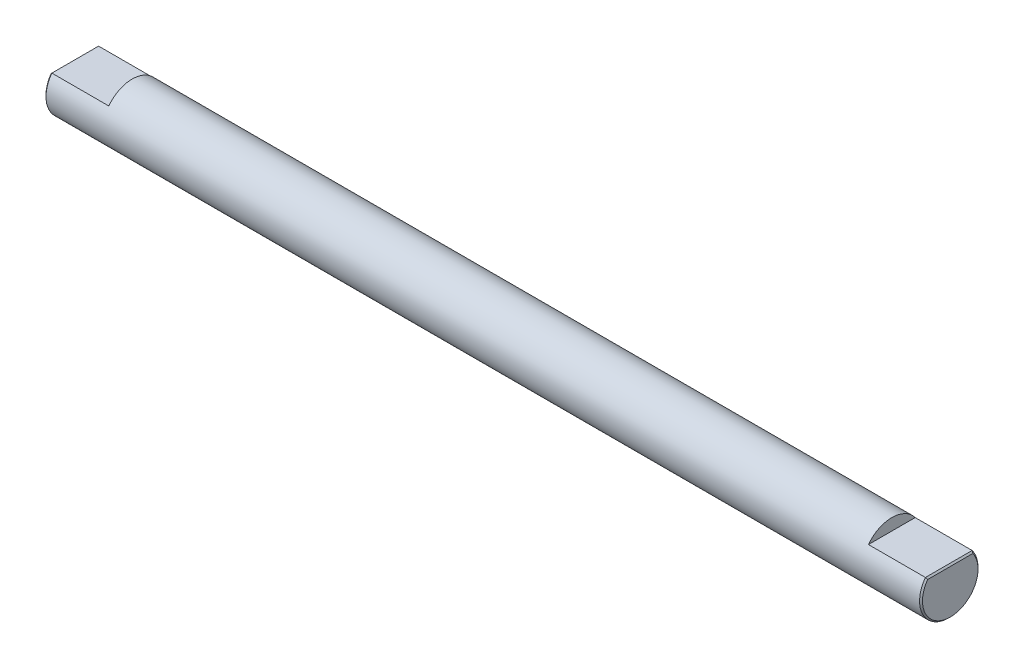
SolidWorks part; units mm, degrees
ref_plane "Front Plane" through (0, 0, 0) normal (0, 0, 1) x (1, 0, 0)
ref_plane "Top Plane" through (0, 0, 0) normal (0, 1, 0) x (1, 0, 0)
ref_plane "Right Plane" through (0, 0, 0) normal (1, 0, 0) x (0, 0, -1)
sketch "Sketch1" plane through (0, 0, 0) normal (0, 0, 1) x (1, 0, 0)
  line L0 (0, 0) -> (300, 0) construction
  line L2 (0, 0) -> (300, 0)
  line L3 (0, 0) -> (0, 10)
  line L4 (0, 10) -> (300, 10)
  line L5 (300, 0) -> (300, 10)
  dimension "D" = 20
  dimension "L" = 300
revolve "Revolve1" add sketch "Sketch1" angle 360 about L0
sketch "Sketch2" plane through (0, 0, 0) normal (0, 0, 1) x (1, 0, 0)
  line L0 (0, 10) -> (300, 10) construction
  line L1 (0, 10) -> (20, 10)
  line L2 (0, 10) -> (0, 6)
  line L3 (0, 6) -> (20, 6)
  line L4 (20, 10) -> (20, 6)
  line L5 (280, 10) -> (300, 10)
  line L6 (280, 10) -> (280, 6)
  line L7 (280, 6) -> (300, 6)
  line L8 (300, 10) -> (300, 6)
  line L9 (0, 0) -> (0, 10) construction
  line L10 (300, 0) -> (300, 10) construction
  line L11 (0, -10) -> (300, -10) construction
  dimension "W" = 16
  dimension "F" = 20
  dimension "T" = 20
  dimension "D" = 20
  dimension "W_R" = 16
extrude "Cut-Extrude1" cut sketch "Sketch2" against normal through all and the other way through all
chamfer "Chamfer1" distance 0.5 angle 45 4 edges at (0, -10, 0) (300, -10, 0) (0, 6, 0) (300, 6, 0)
sketch "Sketch3" [suppressed] plane through (0, 0, 0) normal (0, 0, 1) x (1, 0, 0)
  line L0 (0, 0.5) -> (0, -2.5) construction
  line L1 (4, 3) -> (6, 3)
  line L2 (4, 3) -> (4, 2)
  line L3 (4, 2) -> (6, 2)
  line L4 (6, 3) -> (6, 2)
  line L5 (5, 3) -> (5, 2) construction
  line L7 (0, 3) -> (24, 3) construction
  dimension "H" = 1
  dimension "G" = 2
  dimension "FC" = 4
extrude "Cut-Extrude2" [suppressed] cut sketch "Sketch3" against normal through all and the other way through all
ref_plane "FC_SEC" [suppressed] through (5, 0, 0) normal (1, 0, 0) x (0, 0, -1)
sketch "Sketch4" [suppressed] plane through (0, 0, 0) normal (0, 0, 1) x (1, 0, 0)
  line L0 (5, 3) -> (5, 2) construction
  line L1 (4, 3) -> (6, 3)
  line L2 (4, 3) -> (4, 2)
  line L3 (4, 2) -> (6, 2)
  line L4 (6, 3) -> (6, 2)
  line L5 (18, 3) -> (20, 3)
  line L6 (18, 3) -> (18, 2)
  line L7 (18, 2) -> (20, 2)
  line L8 (20, 3) -> (20, 2)
  line L9 (19, 3) -> (19, 2) construction
  line L10 (0, 3) -> (24, 3) construction
  line L12 (0, 0) -> (0, 3) construction
  line L13 (24, 0) -> (24, 3) construction
  dimension "J" = 2
  dimension "V" = 2
  dimension "H" = 1
  dimension "WFC" = 4
  dimension "W_1" = 4
  dimension "H_R" = 1
extrude "Cut-Extrude3" [suppressed] cut sketch "Sketch4" against normal through all and the other way through all
ref_plane "WFC_SEC1" [suppressed] through (5, 0, 0) normal (1, 0, 0) x (0, 0, -1)
ref_plane "WFC_SEC2" [suppressed] through (19, 0, 0) normal (1, 0, 0) x (0, 0, -1)
sketch "Sketch5" [suppressed] plane through (0, 0, 0) normal (0, 0, 1) x (1, 0, 0)
  line L0 (0, 3) -> (24, 3) construction
  line L1 (3, -2) -> (11, -2)
  line L2 (3, -2) -> (3, -3)
  line L3 (3, -3) -> (11, -3)
  line L4 (11, -2) -> (11, -3)
  line L5 (3, 3) -> (11, 3)
  line L6 (3, 3) -> (3, 2)
  line L7 (3, 2) -> (11, 2)
  line L8 (11, 3) -> (11, 2)
  line L9 (0, 0.5) -> (0, -2.5) construction
  line L10 (24, 0) -> (24, 3) construction
  line L11 (7, -3) -> (7, -2) construction
  line L13 (0, 0) -> (24, 0) construction
  dimension "W_2" = 4
  dimension "L2_s" = 8
  dimension "SC" = 3
extrude "Cut-Extrude4" [suppressed] cut sketch "Sketch5" along normal through all and the other way through all
ref_plane "SC_SEC" [suppressed] through (7, 0, 0) normal (1, 0, 0) x (0, 0, -1)
sketch "Sketch6" [suppressed] plane through (0, 0, 0) normal (0, 0, 1) x (1, 0, 0)
  line L0 (0, 0) -> (24, 0) construction
  line L1 (24, -2.5) -> (24, 0.5) construction
  line L2 (0, 3) -> (24, 3) construction
  line L3 (5.3, 3) -> (6, 3)
  line L4 (5.3, 3) -> (5.3, 2.5)
  line L5 (5.3, 2.5) -> (6, 2.5)
  line L6 (6, 3) -> (6, 2.5)
  line L7 (0, 0.5) -> (0, -2.5) construction
  dimension "D_s" = 5
  dimension "M_s" = 0.7
  dimension "TA" = 6
revolve "Cut-Revolve1" [suppressed] cut sketch "Sketch6" angle 360 about L0
sketch "Sketch7" [suppressed] plane through (0, 0, 0) normal (0, 0, 1) x (1, 0, 0)
  line L0 (0, 3) -> (24, 3) construction
  line L1 (18, 3) -> (18.7, 3)
  line L2 (18, 3) -> (18, 2.5)
  line L3 (18, 2.5) -> (18.7, 2.5)
  line L4 (18.7, 3) -> (18.7, 2.5)
  line L5 (0, 0) -> (24, 0) construction
  line L6 (24, -2.5) -> (24, 0.5) construction
  dimension "D_s" = 5
  dimension "TB" = 6
  dimension "M_s" = 0.7
revolve "Cut-Revolve2" [suppressed] cut sketch "Sketch7" angle 360 about L5
